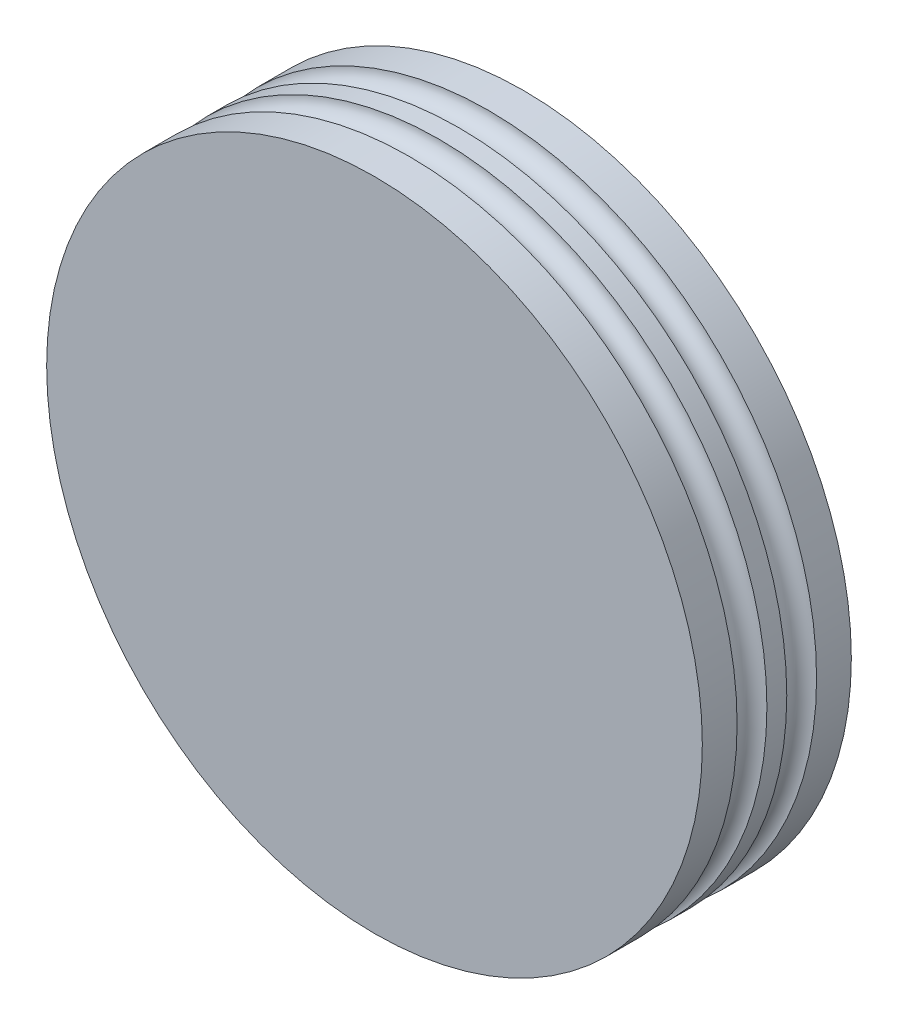
SolidWorks part; units mm, degrees
ref_plane "Alzado" through (0, 0, 0) normal (0, 0, 1) x (1, 0, 0)
ref_plane "Planta" through (0, 0, 0) normal (0, 1, 0) x (1, 0, 0)
ref_plane "Vista lateral" through (0, 0, 0) normal (1, 0, 0) x (0, 0, -1)
sketch "Croquis1" plane through (0, 0, 0) normal (0, 0, 1) x (1, 0, 0)
  line L0 (-5.5345, 0) -> (5.5172, 0) construction
  line L1 (-2.2361, -2) -> (2.2361, -2)
  line L2 (-2.2361, 2) -> (2.2361, 2)
  line L3 (-5.5345, 2) -> (5.5172, 2) construction
  line L4 (-5.5345, -2) -> (5.5172, -2) construction
  arc A0 (-2.2361, 2) -> (-2.2361, -2) centre (0, 0) ccw
  arc A1 (2.2361, -2) -> (2.2361, 2) centre (0, 0) ccw
  circle A2 centre (0, 0) radius 5
  dimension "D1" = 6
  dimension "D4" = 10
  dimension "D2" = 2
  dimension "D3" = 2
extrude "Saliente-Extruir1" add sketch "Croquis1" along normal blind 10
sketch "Croquis2" plane through (0, 0, 10) normal (0, 0, 1) x (1, 0, 0)
  circle A0 centre (0, 0) radius 33
  dimension "D1" = 66
extrude "Saliente-Extruir2" add sketch "Croquis2" along normal blind 15
sketch "Croquis3" plane through (0, 0, 0) normal (0, 1, 0) x (1, 0, 0)
  line L0 (33, -25) -> (33, -10) construction
  line L1 (-33, -25) -> (33, -25) construction
  line L2 (33, -10) -> (-33, -10) construction
  line L3 (0, -24.9789) -> (0, 0) construction
  line L4 (5, 0) -> (-5, 0) construction
  circle A0 centre (33, -15) radius 1.5
  circle A1 centre (33, -20) radius 1.5
  dimension "D3" = 3
  dimension "D4" = 3
  dimension "D1" = 5
  dimension "D2" = 5
revolve "Cortar-Revolución1" cut sketch "Croquis3" angle 360 about L3
